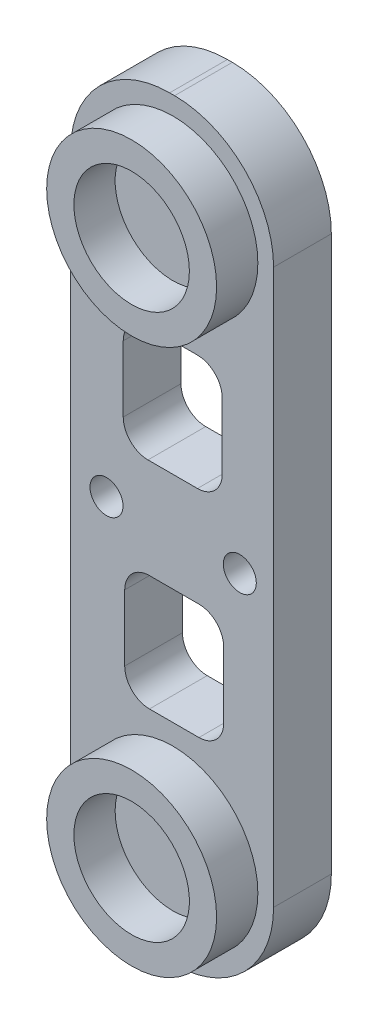
SolidWorks part; units mm, degrees
ref_plane "Front Plane" through (0, 0, 0) normal (0, 0, 1) x (1, 0, 0)
ref_plane "Top Plane" through (0, 0, 0) normal (0, 1, 0) x (1, 0, 0)
ref_plane "Right Plane" through (0, 0, 0) normal (1, 0, 0) x (0, 0, -1)
other "Graphic1"
ref_plane "Plane1" through (0, 0, 10) normal (0, 0, 1) x (1, 0, 0)
sketch "Sketch1" plane through (0, 0, 10) normal (0, 0, 1) x (1, 0, 0)
  line L1 (-301.228, 339.9252) -> (-288.928, 339.9252)
  line L2 (-301.228, 339.9252) -> (-301.228, 294.3252)
  line L3 (-301.228, 294.3252) -> (-288.928, 294.3252)
  line L4 (-288.928, 339.9252) -> (-288.928, 294.3252)
  line L5 (-291.9514, 306.9769) -> (-297.9514, 306.9769)
  line L6 (-291.9514, 306.9769) -> (-291.9514, 313.9769)
  line L7 (-291.9514, 313.9769) -> (-297.9514, 313.9769)
  line L8 (-297.9514, 306.9769) -> (-297.9514, 313.9769)
  line L9 (-292.0408, 320.0028) -> (-298.0408, 320.0028)
  line L10 (-292.0408, 320.0028) -> (-292.0408, 327.0028)
  line L11 (-292.0408, 327.0028) -> (-298.0408, 327.0028)
  line L12 (-298.0408, 320.0028) -> (-298.0408, 327.0028)
  circle A0 centre (-290.9753, 316.8223) radius 1
  circle A1 centre (-299.0535, 316.8223) radius 1
  point P12 (-292.0408, 320.0028)
  dimension "D3" = 6
  dimension "D1" = 12.3
  dimension "D2" = 45.6
  dimension "D4" = 7
  dimension "D5" = 6
  dimension "D6" = 7
extrude "Boss-Extrude1" add sketch "Sketch1" along normal blind 3.5
fillet "Fillet1" radius 6 4 edges at (-288.928, 339.9252, 11.75) (-301.228, 339.9252, 11.75) (-288.928, 294.3252, 11.75) (-301.228, 294.3252, 11.75)
fillet "Fillet2" radius 1.5 8 edges at (-297.9514, 306.9769, 11.75) (-291.9514, 306.9769, 11.75) (-291.9514, 313.9769, 11.75) (-297.9514, 313.9769, 11.75) (-298.0408, 327.0028, 11.75) (-292.0408, 320.0028, 11.75) (-298.0408, 320.0028, 11.75) (-292.0408, 327.0028, 11.75)
sketch "Sketch2" plane through (0, 0, 13.5) normal (0, 0, 1) x (1, 0, 0)
  line L0 (-288.928, 317.1252) -> (-280.0834, 317.1252) construction
  line L1 (-288.928, 300.3252) -> (-288.928, 333.9252) construction
  circle A0 centre (-295.0313, 333.6611) radius 3.5
  circle A1 centre (-295.0313, 333.6611) radius 5.15
  circle A2 centre (-295.0313, 300.5893) radius 5.15
  circle A3 centre (-295.0313, 300.5893) radius 3.5
extrude "Boss-Extrude2" add sketch "Sketch2" along normal blind 2.5
